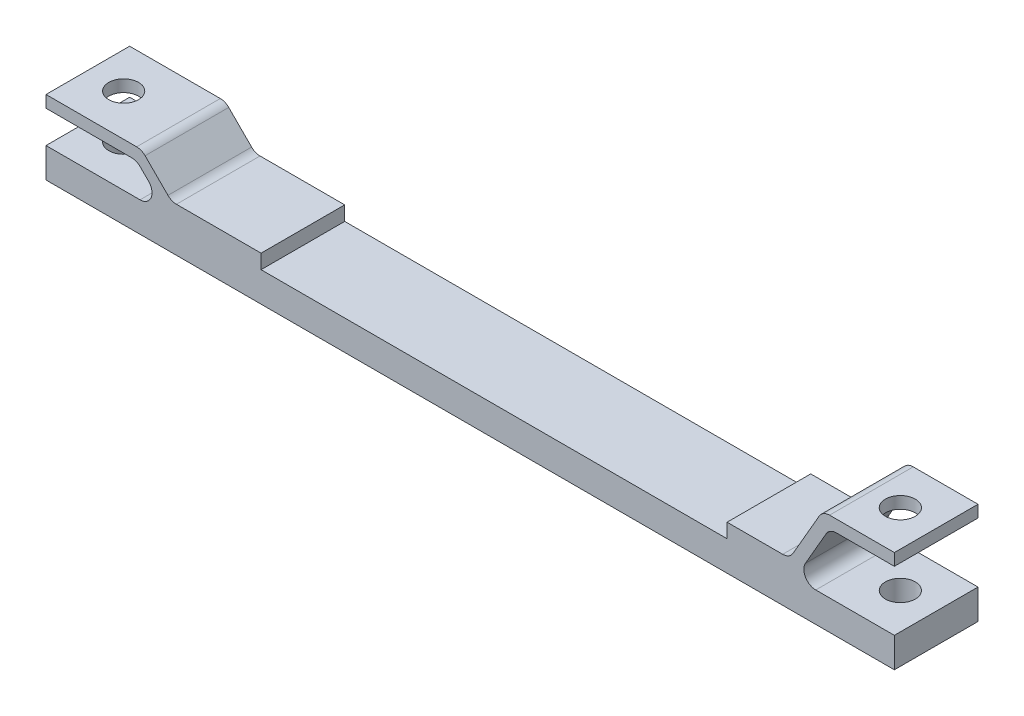
SolidWorks part; units mm, degrees
ref_plane "Front Plane" through (0, 0, 0) normal (0, 0, 1) x (1, 0, 0)
ref_plane "Top Plane" through (0, 0, 0) normal (0, 1, 0) x (1, 0, 0)
ref_plane "Right Plane" through (0, 0, 0) normal (1, 0, 0) x (0, 0, -1)
sketch "Sketch1" plane through (0, 0, 0) normal (0, 0, 1) x (1, 0, 0)
  line L0 (0, 78) -> (113.7868, 78)
  line L1 (0, 0) -> (1065, 0)
  line L2 (0, 0) -> (0, 37.5)
  line L3 (0, 37.5) -> (1065, 37.5)
  line L4 (1065, 0) -> (1065, 37.5)
  line L5 (0, 93) -> (120, 93)
  line L6 (120, 93) -> (157.5, 55.5)
  line L7 (157.5, 55.5) -> (270, 55.5)
  line L8 (270, 55.5) -> (270, 37.5)
  line L9 (113.7868, 78) -> (146.8934, 44.8934)
  line L10 (1065, 127.5) -> (975, 127.5)
  line L11 (975, 127.5) -> (933.4308, 55.5)
  line L12 (933.4308, 55.5) -> (855, 55.5)
  line L13 (855, 55.5) -> (855, 37.5)
  line L14 (1065, 112.5) -> (983.6603, 112.5)
  line L15 (983.6603, 112.5) -> (946.4212, 48)
  line L16 (1065, 112.5) -> (1065, 127.5)
  line L17 (946.4212, 48) -> (940.9226, 37.5)
  line L18 (146.8934, 44.8934) -> (154.2868, 37.5)
  line L19 (0, 78) -> (0, 93)
  dimension "D1" = 1065
  dimension "D2" = 37.5
  dimension "D3" = 55.5
  dimension "D4" = 120
  dimension "D5" = 18
  dimension "D6" = 45
  dimension "D7" = 270
  dimension "D8" = 90
  dimension "D9" = 90
  dimension "D10" = 60
  dimension "D11" = 18
  dimension "D12" = 210
  dimension "D13" = 15
  dimension "D14" = 15
extrude "Boss-Extrude3" add sketch "Sketch1" against normal blind 105 contours L17 L15 L14 L16 L10 L11 L12 L13 L3 | L19 L0 L9 L18 L3 L8 L7 L6 L5
fillet "Fillet4" radius 15 4 edges at (157.5, 55.5, -52.5) (120, 93, -52.5) (940.9226, 37.5, -52.5) (975, 127.5, -52.5)
fillet "Fillet5" radius 15 1 edges at (113.7868, 78, -52.5)
fillet "Fillet6" radius 15 1 edges at (154.2868, 37.5, -52.5)
fillet "Fillet7" radius 15 1 edges at (933.4308, 55.5, -52.5)
fillet "Fillet8" radius 15 1 edges at (983.6603, 112.5, -52.5)
sketch "Sketch2" plane through (0, 93, 0) normal (0, 1, 0) x (1, 0, 0)
  line L0 (1065, 105) -> (1065, 0) construction
  line L1 (0, 105) -> (0, 0) construction
  circle A0 centre (45, 52.5) radius 18.75
  circle A1 centre (1020, 52.5) radius 18.75
  point P6 (1065, 52.5)
  point P9 (0, 52.5)
  dimension "D1" = 37.5
  dimension "D2" = 37.5
  dimension "D3" = 45
  dimension "D4" = 45
extrude "Cut-Extrude3" cut sketch "Sketch2" against normal through all both and the other way through all
